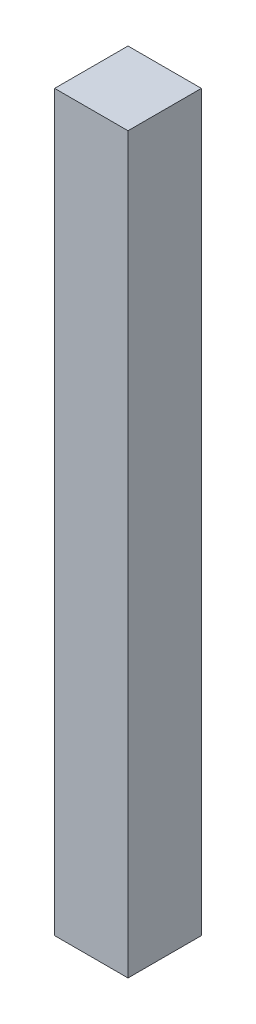
SolidWorks part; units mm, degrees
ref_plane "前视基准面" through (0, 0, 0) normal (0, 0, 1) x (1, 0, 0)
ref_plane "上视基准面" through (0, 0, 0) normal (0, 1, 0) x (1, 0, 0)
ref_plane "右视基准面" through (0, 0, 0) normal (1, 0, 0) x (0, 0, -1)
other "Configuration Table"
sketch "草图1" plane through (0, 0, 0) normal (0, 1, 0) x (1, 0, 0)
  line L1 (0, 0) -> (20, 0)
  line L2 (0, 0) -> (0, -20)
  line L3 (0, -20) -> (20, -20)
  line L4 (20, 0) -> (20, -20)
  dimension "D1" = 20
  dimension "D2" = 20
extrude "凸台-拉伸1" add sketch "草图1" along normal blind 200
